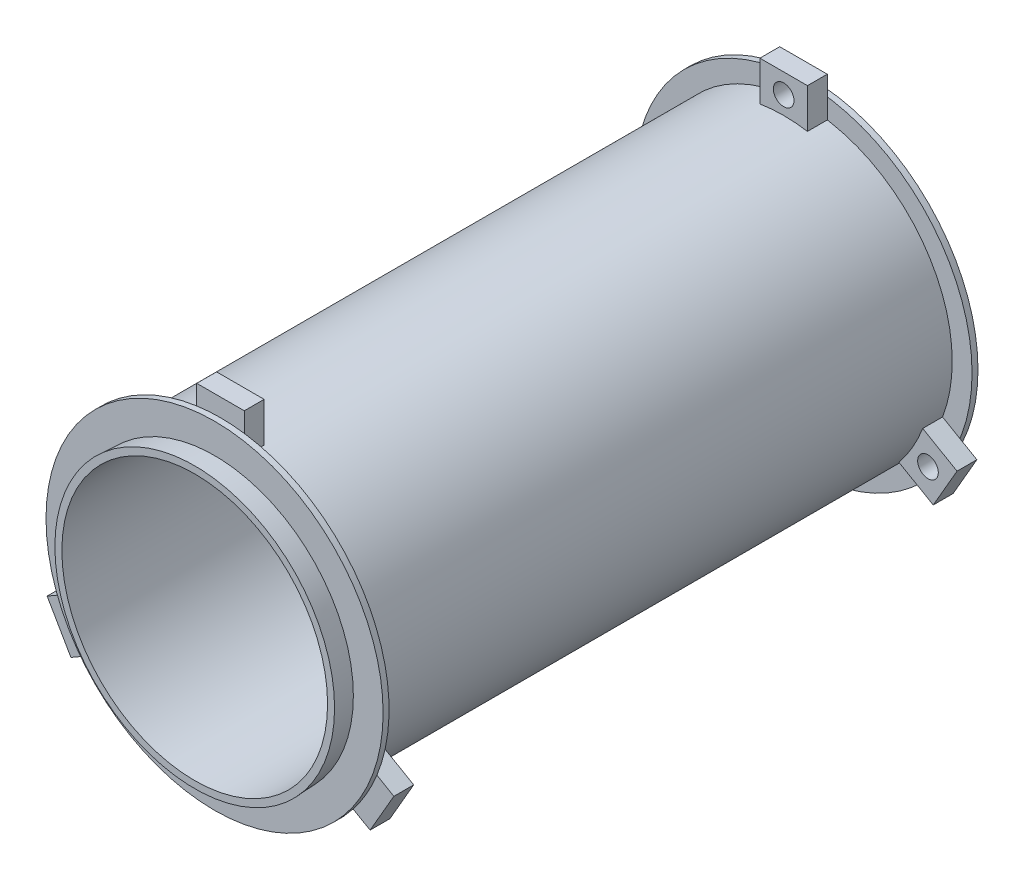
SolidWorks part; units mm, degrees
other "Markup1"
sketch "Sketch38" plane through (-85, -85, 0) normal (-1, 0, 0) x (0, 0, 1)
other "Markup2"
sketch "Sketch39" plane through (-85, -85, 0) normal (-1, 0, 0) x (0, 0, 1)
ref_plane "Front Plane" through (0, 0, 0) normal (0, 0, 1) x (1, 0, 0)
ref_plane "Top Plane" through (0, 0, 0) normal (0, 1, 0) x (1, 0, 0)
ref_plane "Right Plane" through (0, 0, 0) normal (1, 0, 0) x (0, 0, -1)
sketch "Sketch3" plane through (0, 0, 0) normal (0, 0, 1) x (1, 0, 0)
  circle A0 centre (0, 0) radius 75
extrude "Main Body" add sketch "Sketch3" along normal blind 300
sketch "Sketch15" plane through (0, 0, 300) normal (0, 0, 1) x (1, 0, 0)
  circle A0 centre (0, 0) radius 65
sketch "Sketch16" plane through (0, 0, 300) normal (0, 0, 1) x (1, 0, 0)
  circle A0 centre (0, 0) radius 70
extrude "Extension 1" add sketch "Sketch16" along normal blind 10 draft 3 contours A0 draft outward yes
sketch "Sketch23" plane through (0, 0, 310) normal (0, 0, 1) x (1, 0, 0)
  circle A0 centre (0, 0) radius 67
extrude "Cut-Extrude11" cut sketch "Sketch23" against normal blind 333
ref_plane "Top v2" through (0, 0, 310) normal (0, 0, 1) x (1, 0, 0)
ref_plane "Upper circle plane" through (0, 0, 300) normal (0, 0, 1) x (1, 0, 0)
sketch "Sketch35" plane through (0, 0, 0) normal (1, 0, 0) x (0, 0, -1)
  line L0 (28.7866, 0) -> (-339.5902, 0) construction
  line L1 (-300, 75) -> (-297, 75)
  line L2 (-300, 75) -> (-300, 85)
  line L3 (-300, 85) -> (-297, 85)
  line L4 (-297, 75) -> (-297, 85)
  dimension "D1" = 3
  dimension "D2" = 10
revolve "Revolve7" add sketch "Sketch35" angle 360 about L0
sketch "Sketch37" plane through (0, 0, 0) normal (1, 0, 0) x (0, 0, -1)
  line L0 (-339.5784, 0) -> (37.0525, 0) construction
  line L2 (0, 75) -> (-3, 75)
  line L3 (0, 75) -> (0, 85)
  line L4 (0, 85) -> (-3, 85)
  line L5 (-3, 75) -> (-3, 85)
  dimension "D1" = 3
  dimension "D2" = 10
revolve "Revolve11" add sketch "Sketch37" angle 360 about L0
sketch "Sketch41" plane through (0, 0, 310) normal (0, 0, 1) x (1, 0, 0)
  line L0 (0, 0) -> (95.8024, 95.8024) construction
  line L1 (95.8024, 95.8024) -> (-92.7934, -92.7934) construction
  line L2 (-92.7934, -92.7934) -> (0, 0) construction
  line L3 (0, 0) -> (-92.7934, 92.7934) construction
  line L4 (-92.7934, 92.7934) -> (92.7934, -92.7934) construction
  line L5 (119.3768, 0) -> (-118.9211, 0) construction
  line L6 (-118.9211, 0) -> (0, 0) construction
  line L7 (0, 0) -> (0, 113.079) construction
  line L8 (0, 113.079) -> (0, -92.7934) construction
sketch "Sketch46" plane through (0, 0, 0) normal (0, 0, 1) x (1, 0, 0)
  circle A0 centre (0, 0) radius 70
extrude "Extension 2" add sketch "Sketch46" against normal blind 10 draft 3 draft outward yes
sketch "Sketch47" plane through (0, 0, 0) normal (0, 0, 1) x (1, 0, 0)
  circle A0 centre (0, 0) radius 67
extrude "Cut-Extrude16" cut sketch "Sketch47" along normal blind 34 and the other way blind 64
sketch "Sketch49" plane through (0, 0, 297) normal (0, 0, 1) x (1, 0, 0)
  line L0 (0, 85) -> (0, 0)
  line L2 (0, 0.0209) -> (-105.1385, -60.6809)
  line L4 (-0.0181, 0.0105) -> (105.1129, -60.687)
  line L6 (-11.9968, 74.0302) -> (-11.9968, 94.0302)
  line L8 (11.9968, 74.0302) -> (11.9968, 94.0302)
  line L9 (-11.9968, 94.0302) -> (11.9968, 94.0302)
  line L10 (11.9968, 94.0302) -> (11.9968, 74.0302)
  circle A0 centre (0, 0) radius 85 construction
  arc A1 (-11.9968, 74.0302) -> (11.9968, 74.0302) centre (0, 0.3138) cw
  point P9 (0, 75)
  dimension "D4" = 20
ref_plane "Top V3" through (0, 0, -10) normal (0, 0, -1) x (-1, 0, 0)
ref_plane "Middle" through (0, 0, 150) normal (0, 0, 1) x (1, 0, 0)
extrude "RodeHolder" add sketch "Sketch49" against normal blind 10
ref_plane "Plane3" through (0, 0, 287) normal (0, 0, -1) x (-1, 0, 0)
sketch "Sketch55" plane through (0, 0, 287) normal (0, 0, -1) x (-1, 0, 0)
  line L0 (-11.9968, 84.0322) -> (11.9968, 84.0322)
  line L1 (-11.9968, 74.0343) -> (-11.9968, 94.0302) construction
  line L2 (0, 99.3861) -> (0, 69.8701)
  line L3 (11.9968, 74.0343) -> (11.9968, 94.0302) construction
  circle A2 centre (0, 84.0322) radius 5.2
extrude "RodeHolderHole" cut sketch "Sketch55" against normal blind 8
mirror "RodeHolderMirror" about plane through (0, 0, 150) normal (0, 0, 1) of "RodeHolderHole", "RodeHolder"
sketch "Sketch56" plane through (0, 0, 287) normal (0, 0, 1) x (1, 0, 0)
  line L0 (0, 115.843) -> (0, 0) construction
  line L1 (0, 0) -> (125.4946, -72.4543) construction
  line L5 (0, 0) -> (-125.4946, -72.4543) construction
  circle A1 centre (0, 0) radius 70
  dimension "D1" = 120
  dimension "D2" = 120
pattern_circular "RodeHolderPattern" count 3 over 360 about axis through (0, 0, 0) along (0, 0, 1) of "RodeHolder", "RodeHolderMirror", "RodeHolderHole"
sketch "UpperHolderHole (optional)" plane through (0, 94.0302, 0) normal (0, 1, 0) x (1, 0, 0)
  line L0 (11.9968, -292) -> (-11.9968, -292) construction
  line L1 (11.9968, -287) -> (11.9968, -297) construction
  line L2 (-11.9968, -287) -> (-11.9968, -297) construction
  line L3 (-11.9968, -292) -> (0, -292) construction
  line L4 (0, -292) -> (0, -287) construction
  line L5 (-11.9968, -287) -> (11.9968, -287) construction
  line L6 (0, -287) -> (0, -297) construction
  line L7 (-11.9968, -297) -> (11.9968, -297) construction
  circle A0 centre (0, -292) radius 1.5
  dimension "D1" = 3
